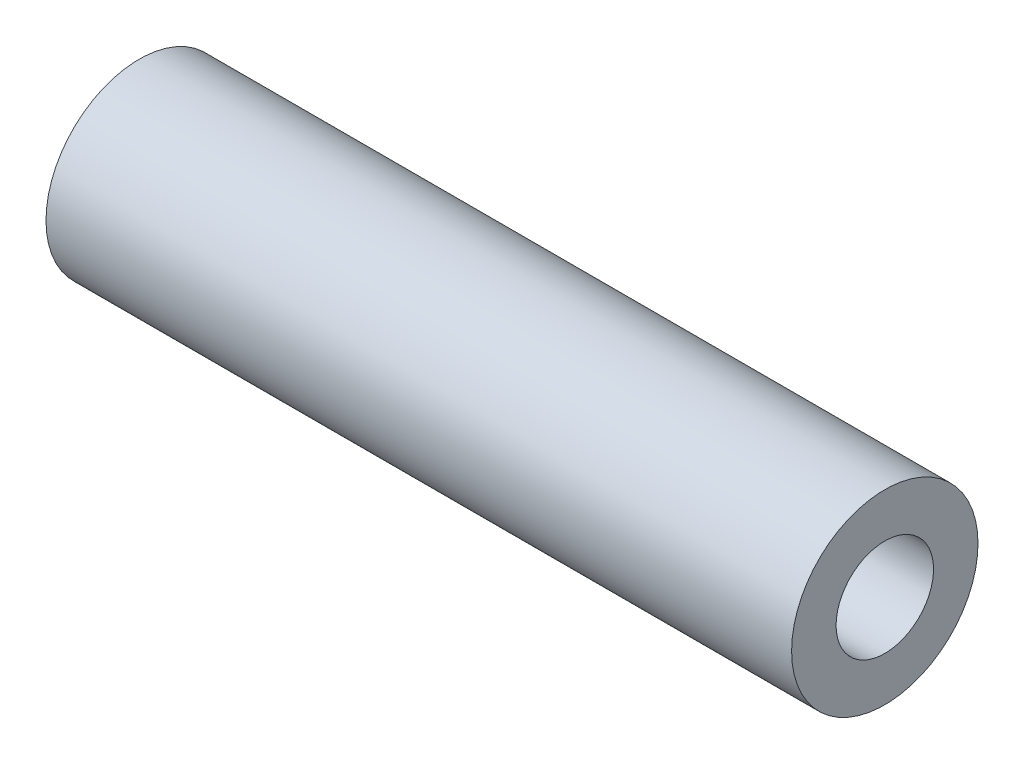
SolidWorks part; units mm, degrees
material "6061-T6 (SS)"
ref_plane "Front Plane" through (0, 0, 0) normal (0, 0, 1) x (1, 0, 0)
ref_plane "Top Plane" through (0, 0, 0) normal (0, 1, 0) x (1, 0, 0)
ref_plane "Right Plane" through (0, 0, 0) normal (1, 0, 0) x (0, 0, -1)
sketch "Sketch1" plane through (0, 0, 0) normal (1, 0, 0) x (0, 0, -1)
  circle A0 centre (0, 0) radius 4.7625
  circle A1 centre (0, 0) radius 2.4892
  dimension "D1" = 4.9784
  dimension "D2" = 9.525
extrude "Boss-Extrude1" add sketch "Sketch1" along normal mid plane 38.1
